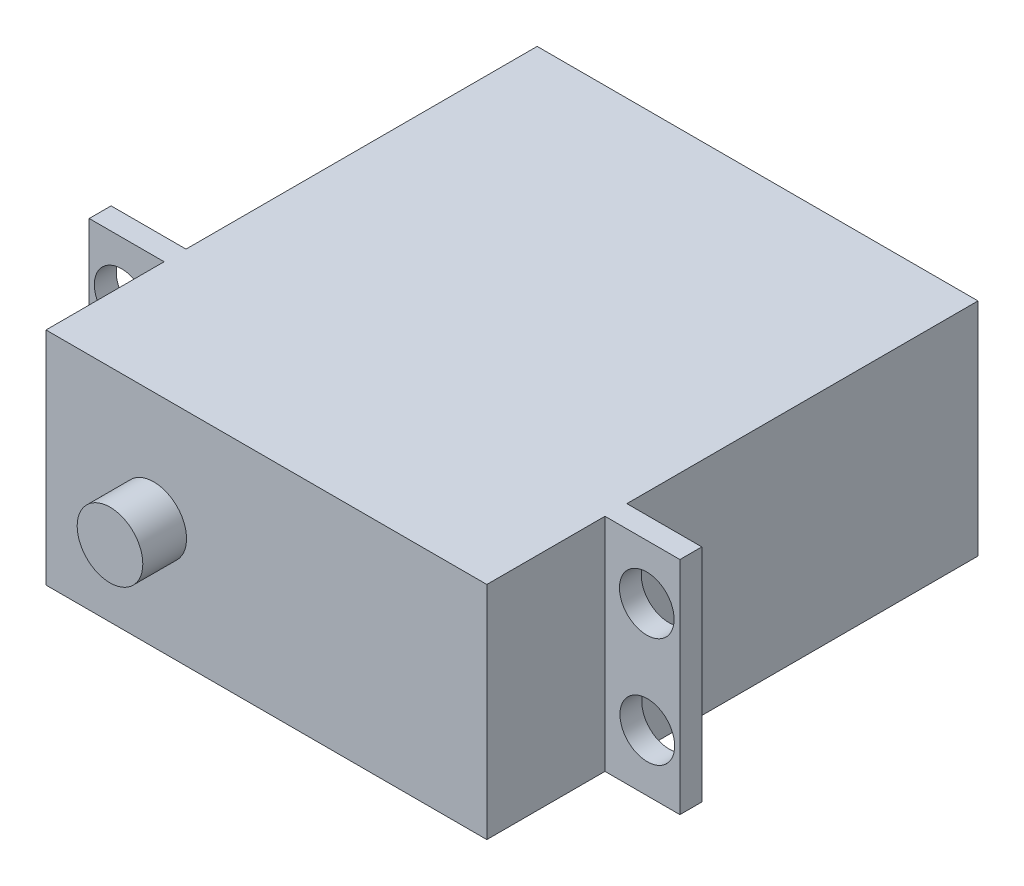
SolidWorks part; units mm, degrees
ref_plane "Plan de face" through (0, 0, 0) normal (0, 0, 1) x (1, 0, 0)
ref_plane "Plan de dessus" through (0, 0, 0) normal (0, 1, 0) x (1, 0, 0)
ref_plane "Plan de droite" through (0, 0, 0) normal (1, 0, 0) x (0, 0, -1)
sketch "Esquisse1" plane through (0, 0, 0) normal (0, 0, 1) x (1, 0, 0)
  line L1 (0, 15.5912) -> (40.3, 15.5912)
  line L2 (0, 15.5912) -> (0, -4.6088)
  line L3 (0, -4.6088) -> (40.3, -4.6088)
  line L4 (40.3, 15.5912) -> (40.3, -4.6088)
  dimension "D1" = 40.3
  dimension "D2" = 20.2
extrude "Boss.-Extru.1" add sketch "Esquisse1" along normal blind 32.1
sketch "Esquisse2" plane through (0, 0, 32.1) normal (0, 0, 1) x (1, 0, 0)
  line L0 (0, -4.6088) -> (40.3, -4.6088) construction
  line L1 (-6.85, 15.5912) -> (47.15, 15.5912)
  line L2 (-6.85, 15.5912) -> (-6.85, -4.6088)
  line L3 (-6.85, -4.6088) -> (47.15, -4.6088)
  line L4 (47.15, 15.5912) -> (47.15, -4.6088)
  line L5 (40.3, 15.5912) -> (0, 15.5912) construction
  line L6 (0, 15.5912) -> (0, -4.6088) construction
  dimension "D1" = 54
  dimension "D2" = 0
  dimension "D3" = 0
  dimension "D4" = 6.85
extrude "Boss.-Extru.2" add sketch "Esquisse2" along normal blind 2
sketch "Esquisse3" plane through (0, 0, 34.1) normal (0, 0, 1) x (1, 0, 0)
  line L0 (-6.85, -4.6088) -> (47.15, -4.6088) construction
  line L1 (0, -4.6088) -> (40.3, -4.6088)
  line L2 (0, -4.6088) -> (0, 15.5912)
  line L3 (0, 15.5912) -> (40.3, 15.5912)
  line L4 (40.3, -4.6088) -> (40.3, 15.5912)
  line L5 (47.15, 15.5912) -> (-6.85, 15.5912) construction
  line L6 (47.15, -4.6088) -> (47.15, 15.5912) construction
  line L7 (-6.85, 15.5912) -> (-6.85, -4.6088) construction
  dimension "D1" = 6.85
  dimension "D2" = 6.85
extrude "Boss.-Extru.3" add sketch "Esquisse3" along normal blind 10.8
sketch "Esquisse4" plane through (0, 0, 44.9) normal (0, 0, 1) x (1, 0, 0)
  line L0 (40.3, 15.5912) -> (0, 15.5912) construction
  line L3 (0, 15.5912) -> (0, -4.6088) construction
  circle A0 centre (9.85, 5.4912) radius 3
  dimension "D1" = 10.1
  dimension "D2" = 9.85
  dimension "D3" = 6
extrude "Boss.-Extru.4" add sketch "Esquisse4" along normal blind 4
sketch "Esquisse5" plane through (0, 0, 34.1) normal (0, 0, 1) x (1, 0, 0)
  line L4 (47.15, 15.5912) -> (40.3, 15.5912) construction
  line L5 (0, 15.5912) -> (-6.85, 15.5912) construction
  line L8 (47.15, -4.6088) -> (47.15, 15.5912) construction
  circle A0 centre (-3.88, 10.5912) radius 2.5
  circle A1 centre (-3.8321, 0.5913) radius 2.5
  circle A2 centre (44.12, 10.5912) radius 2.5
  circle A3 centre (44.1679, 0.5913) radius 2.5
  dimension "D1" = 5
  dimension "D2" = 5
  dimension "D4" = 10
  dimension "D6" = 5
  dimension "D8" = 5
  dimension "D9" = 5
  dimension "D10" = 48
  dimension "D3" = 10
  dimension "D5" = 48
  dimension "D7" = 5
  dimension "D11" = 3.03
extrude "Enlèv. mat.-Extru.1" cut sketch "Esquisse5" against normal blind 4
